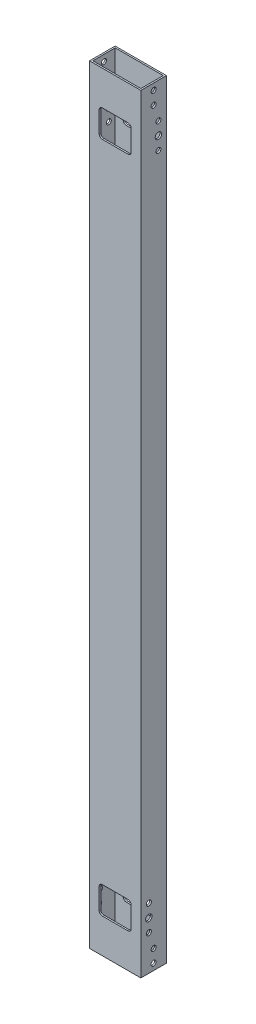
SolidWorks part; units mm, degrees
ref_plane "Front Plane" through (0, 0, 0) normal (0, 0, 1) x (1, 0, 0)
ref_plane "Top Plane" through (0, 0, 0) normal (0, 1, 0) x (1, 0, 0)
ref_plane "Right Plane" through (0, 0, 0) normal (1, 0, 0) x (0, 0, -1)
sketch "Sketch1" plane through (0, 0, 0) normal (0, 0, 1) x (1, 0, 0)
  line L1 (-25.4, -381) -> (25.4, -381)
  line L2 (-25.4, -381) -> (-25.4, 381)
  line L3 (-25.4, 381) -> (25.4, 381)
  line L4 (25.4, -381) -> (25.4, 381)
  line L5 (-25.4, -381) -> (25.4, 381) construction
  line L6 (-25.4, 381) -> (25.4, -381) construction
  point P0 (0, 0)
  dimension "D1" = 50.8
  dimension "D2" = 762
extrude "Boss-Extrude1" add sketch "Sketch1" along normal mid plane 25.4
shell "Shell1" thickness 1.5875
sketch "Sketch3" plane through (0, 0, 0) normal (1, 0, 0) x (0, 0, -1)
  line L0 (-12.7, -381) -> (12.7, -381) construction
  circle A0 centre (0, -374.65) radius 2.4892
  circle A1 centre (0, -361.95) radius 2.4892
  point P6 (0, -381)
  dimension "D1" = 4.9784
  dimension "D2" = 6.35
  dimension "D3" = 12.7
extrude "Cut-Extrude1" cut sketch "Sketch3" against normal through all both and the other way through all
sketch "Sketch4" plane through (0, 0, 0) normal (1, 0, 0) x (0, 0, -1)
  line L0 (12.7, 381) -> (12.7, -381) construction
  line L3 (-12.7, 381) -> (12.7, 381) construction
  line L4 (-12.7, -381) -> (12.7, -381) construction
  line L5 (-12.7, 381) -> (-12.7, -381) construction
  circle A0 centre (4.7625, 333.375) radius 3.175
  circle A1 centre (4.7625, 346.075) radius 2.4892
  circle A2 centre (4.7625, 320.675) radius 2.4892
  circle A3 centre (-4.7625, -333.375) radius 3.175
  circle A4 centre (-4.7625, -320.675) radius 2.4892
  circle A5 centre (-4.7625, -346.075) radius 2.4892
  dimension "D1" = 6.35
  dimension "D4" = 4.9784
  dimension "D7" = 6.35
  dimension "D8" = 4.9784
  dimension "D2" = 7.9375
  dimension "D5" = 12.7
  dimension "D6" = 12.7
  dimension "D3" = 47.625
  dimension "D9" = 12.7
  dimension "D10" = 12.7
  dimension "D11" = 47.625
  dimension "D12" = 7.9375
extrude "Cut-Extrude2" cut sketch "Sketch4" against normal through all both and the other way through all
mirror "Mirror1" about plane through (0, 0, 0) normal (0, 1, 0) of "Cut-Extrude1"
sketch "Sketch5" plane through (0, 0, 0) normal (0, 0, 1) x (1, 0, 0)
  line L0 (-25.4, -381) -> (25.4, -381) construction
  line L1 (-15.875, -319.8813) -> (15.875, -319.8813)
  line L2 (-15.875, -319.8813) -> (-15.875, -346.8688)
  line L3 (-15.875, -346.8688) -> (15.875, -346.8688)
  line L4 (15.875, -319.8813) -> (15.875, -346.8688)
  line L5 (-25.4, 0) -> (25.4, 0) construction
  line L6 (25.4, -381) -> (25.4, 381) construction
  line L7 (-25.4, 381) -> (-25.4, -381) construction
  line L8 (15.875, 319.8813) -> (15.875, 346.8688)
  line L9 (-15.875, 346.8688) -> (15.875, 346.8688)
  line L10 (-15.875, 319.8813) -> (-15.875, 346.8688)
  line L11 (-15.875, 319.8813) -> (15.875, 319.8813)
  point P4 (0, -346.8688)
  point P7 (0, -381)
  point P8 (-15.875, -333.375)
  dimension "D1" = 26.9875
  dimension "D2" = 31.75
  dimension "D3" = 47.625
extrude "Cut-Extrude4" cut sketch "Sketch5" against normal through all both and the other way through all
fillet "Fillet1" radius 3.175 16 edges at (-15.875, 319.8813, 11.9062) (-15.875, 319.8813, -11.9062) (-15.875, 346.8688, 11.9062) (15.875, 346.8688, 11.9062) (15.875, 346.8688, -11.9062) (15.875, 319.8813, 11.9062) (15.875, 319.8813, -11.9062) (-15.875, -346.8688, 11.9062) (-15.875, -346.8688, -11.9062) (15.875, -346.8688, 11.9062) (15.875, -346.8688, -11.9062) (15.875, -319.8813, 11.9062) (15.875, -319.8813, -11.9062) (-15.875, -319.8813, 11.9062) (-15.875, -319.8813, -11.9062) (-15.875, 346.8688, -11.9062)
equation "\"D6@Sketch4\"=\"D5@Sketch4\""
